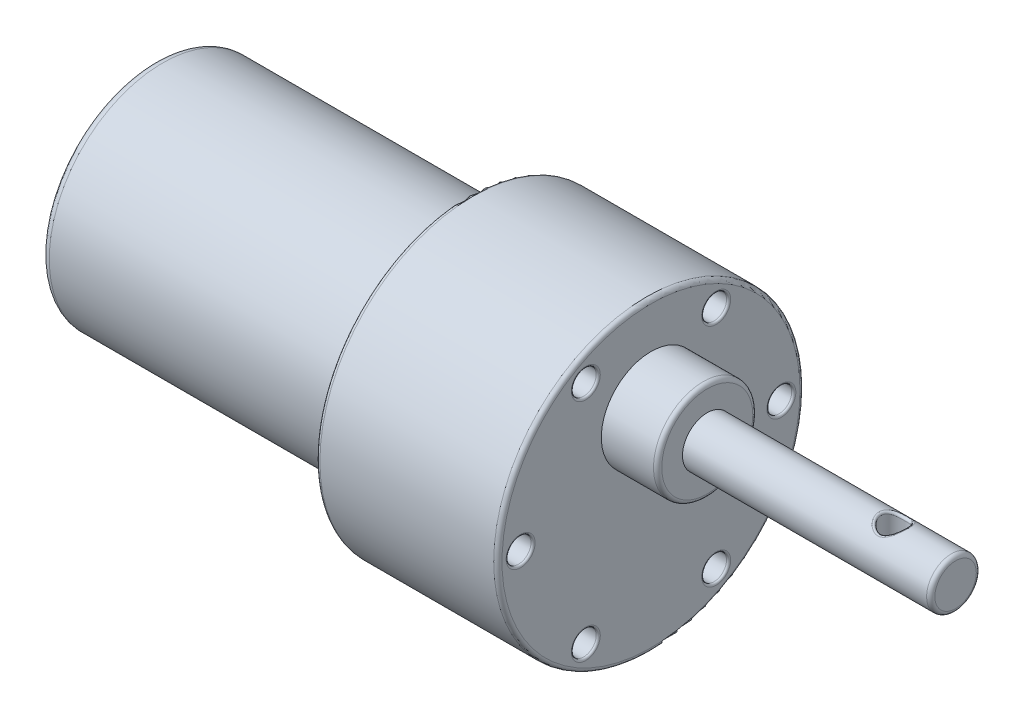
SolidWorks part; units mm, degrees
ref_plane "Front Plane" through (0, 0, 0) normal (0, 0, 1) x (1, 0, 0)
ref_plane "Top Plane" through (0, 0, 0) normal (0, 1, 0) x (1, 0, 0)
ref_plane "Right Plane" through (0, 0, 0) normal (1, 0, 0) x (0, 0, -1)
sketch "Sketch1" plane through (0, 0, 0) normal (1, 0, 0) x (0, 0, -1)
  circle A0 centre (0, 0) radius 13.7
  dimension "D1" = 27.4
extrude "Boss-Extrude1" add sketch "Sketch1" along normal blind 38
fillet "Fillet1" radius 1 2 edges at (0, 0, -13.7) (38, 0, -13.7)
sketch "Sketch2" plane through (38, 0, 0) normal (1, 0, 0) x (0, 0, -1)
  circle A0 centre (0, 0) radius 18.5
  dimension "D1" = 37
extrude "Boss-Extrude2" add sketch "Sketch2" along normal blind 22
fillet "Fillet2" radius 0.5 2 edges at (60, 0, -18.5) (38, 0, -18.5)
sketch "Sketch3" plane through (60, 0, 0) normal (1, 0, 0) x (0, 0, -1)
  circle A0 centre (0, 7) radius 6
  point P2 (0, 0)
  dimension "D1" = 12
  dimension "D2" = 7
extrude "Boss-Extrude3" add sketch "Sketch3" along normal blind 6.8
sketch "Sketch4" plane through (66.8, 0, 0) normal (1, 0, 0) x (0, 0, -1)
  circle A0 centre (0, 7) radius 3
  dimension "D1" = 6
extrude "Boss-Extrude4" add sketch "Sketch4" along normal blind 30
sketch "Sketch5" plane through (60, 0, 0) normal (1, 0, 0) x (0, 0, -1)
  circle A1 centre (15.75, 0) radius 1.5
  circle A2 centre (7.875, -13.6399) radius 1.5
  circle A3 centre (-7.875, -13.6399) radius 1.5
  circle A4 centre (-15.75, 0) radius 1.5
  circle A5 centre (-7.875, 13.6399) radius 1.5
  circle A6 centre (7.875, 13.6399) radius 1.5
  dimension "D1" = 15.75
  dimension "D2" = 3
  dimension "D3" = 6
extrude "Cut-Extrude1" cut sketch "Sketch5" against normal blind 15
fillet "Fillet3" radius 0.5 2 edges at (66.8, 7, -6) (96.8, 7, -3)
sketch "Sketch6" plane through (0, 0, 0) normal (0, 1, 0) x (1, 0, 0)
  line L0 (96.8, -2.5) -> (96.8, 2.5) construction
  circle A0 centre (89.3, 0) radius 1.5
  point P2 (0, 0)
  dimension "D1" = 3
  dimension "D2" = 7.5
extrude "Cut-Extrude2" cut sketch "Sketch6" along normal up to next
sketch "Sketch7" plane through (0, 0, 0) normal (-1, 0, 0) x (0, 0, 1)
  line L0 (0, 0) -> (0, 12.7) construction
  line L1 (-9.5, -1.25) -> (-10.5, -1.25)
  line L2 (9.5, 1.25) -> (10.5, 1.25)
  line L3 (9.5, 1.25) -> (9.5, -1.25)
  line L4 (9.5, -1.25) -> (10.5, -1.25)
  line L5 (10.5, 1.25) -> (10.5, -1.25)
  line L6 (9.5, 1.25) -> (10.5, -1.25) construction
  line L7 (9.5, -1.25) -> (10.5, 1.25) construction
  line L8 (-10.5, 1.25) -> (-10.5, -1.25)
  line L9 (-9.5, 1.25) -> (-10.5, 1.25)
  line L10 (-9.5, 1.25) -> (-9.5, -1.25)
  circle A0 centre (0, 0) radius 1
  circle A1 centre (0, 0) radius 12.7 construction
  point P4 (10, 0)
  point P6 (0, 0)
  dimension "D1" = 2
  dimension "D2" = 1
  dimension "D3" = 2.5
  dimension "D4" = 10
extrude "Boss-Extrude5" add sketch "Sketch7" along normal blind 2
fillet "Fillet4" radius 1 1 edges at (-2, 0, 1)
sketch "Sketch8" plane through (0, 0, 10.5) normal (0, 0, 1) x (1, 0, 0)
  line L0 (-2, 1.25) -> (0, 1.25) construction
  circle A0 centre (-1, 0) radius 0.5
  point P2 (0, 0)
  point P4 (0, 0)
  point P7 (-1, 1.25)
  dimension "D1" = 1
extrude "Cut-Extrude3" cut sketch "Sketch8" against normal up to surface (1 mm away) up to face at (-1, 0, 9.5)
sketch "Sketch9" plane through (0, 0, -10.5) normal (0, 0, -1) x (-1, 0, 0)
  line L0 (2, -1.25) -> (0, -1.25) construction
  circle A0 centre (1, 0) radius 0.5
  point P2 (0, 0)
  point P4 (0, 0)
  point P7 (1, -1.25)
  dimension "D1" = 1
extrude "Cut-Extrude4" cut sketch "Sketch9" against normal up to surface (1 mm away) up to face at (-1, 0, -9.5)
fillet "Fillet5" radius 0.25 2 edges at (89.4602, 4.397, 1.4914) (89.1398, 9.603, 1.4914)
fillet "Fillet6" radius 0.25 6 edges at (60, 13.6399, 6.375) (60, 0, 14.25) (60, -13.6399, 6.375) (60, -13.6399, -9.375) (60, 0, -17.25) (60, 13.6399, -9.375)
